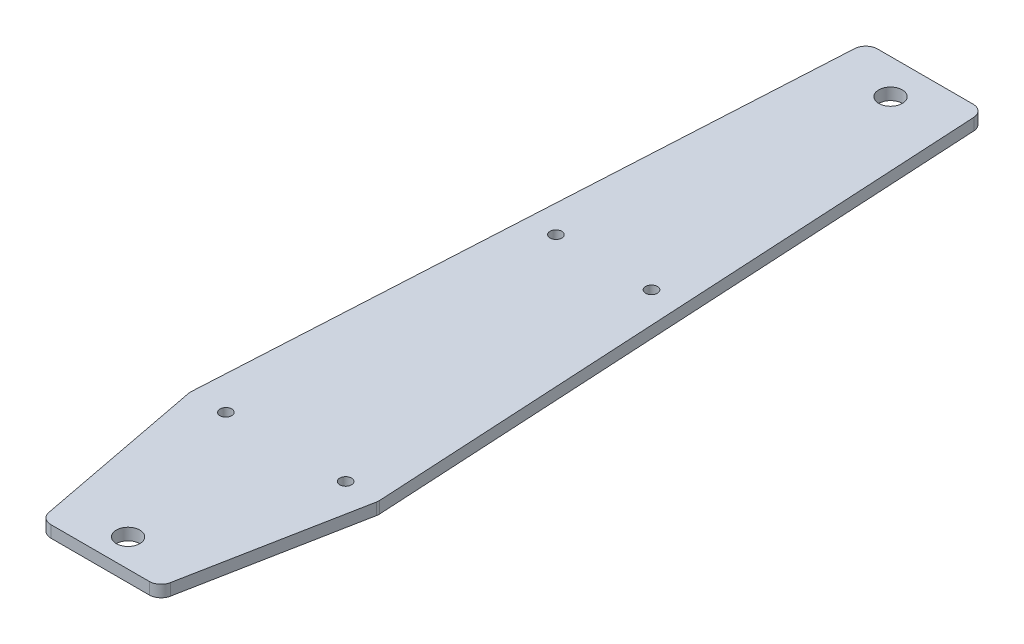
SolidWorks part; units mm, degrees
ref_plane "Front Plane" through (0, 0, 0) normal (0, 0, 1) x (1, 0, 0)
ref_plane "Top Plane" through (0, 0, 0) normal (0, 1, 0) x (1, 0, 0)
ref_plane "Right Plane" through (0, 0, 0) normal (1, 0, 0) x (0, 0, -1)
sketch "Sketch1" plane through (0, 0, 0) normal (0, 1, 0) x (1, 0, 0)
  line L1 (4.1301, 0) -> (45.8699, 0)
  line L3 (4.7319, 350) -> (45.2681, 350)
  line L5 (-0.7799, 4.0558) -> (-14.8837, 77.4003)
  line L6 (-0.2606, 345.2753) -> (-14.9661, 78.6198)
  line L7 (50.2606, 345.2753) -> (64.9661, 78.6198)
  line L8 (50.7799, 4.0558) -> (64.8837, 77.4003)
  arc A0 (-14.9661, 78.6198) -> (-14.8837, 77.4003) centre (-9.9737, 78.3444) ccw
  arc A1 (-14.9661, 78.6198) -> (-14.8837, 77.4003) centre (-9.9737, 78.3444) ccw
  arc A2 (64.8837, 77.4003) -> (64.9661, 78.6198) centre (59.9737, 78.3444) ccw
  arc A3 (-0.2606, 345.2753) -> (4.7319, 350) centre (4.7319, 345) cw
  arc A4 (45.2681, 350) -> (50.2606, 345.2753) centre (45.2681, 345) cw
  arc A5 (4.1301, 0) -> (-0.7799, 4.0558) centre (4.1301, 5) cw
  arc A6 (45.8699, 0) -> (50.7799, 4.0558) centre (45.8699, 5) ccw
  circle A8 centre (50.7799, 78.3444) radius 2.5
  circle A9 centre (0, 78.3444) radius 2.5
  circle A10 centre (25, 11.8768) radius 5
  circle A11 centre (45.2681, 213.5895) radius 2.5
  circle A12 centre (4.7319, 213.5895) radius 2.5
  circle A13 centre (25, 335.2393) radius 5
  point P9 (-15, 78.0049)
  point P15 (65, 78.0049)
  point P20 (50, 350)
  point P23 (0, 0)
  point P26 (50, 0)
  dimension "D4" = 5
  dimension "D5" = 5
  dimension "D6" = 5
  dimension "D7" = 5
  dimension "D1" = 350
  dimension "D2" = 50
  dimension "D3" = 80
extrude "Boss-Extrude1" add sketch "Sketch1" along normal blind 5 contours L1 A6 L8 A2 L7 A4 L3 A3 L6 A0 L5 A5 A12 A11 A10 A9 A8
